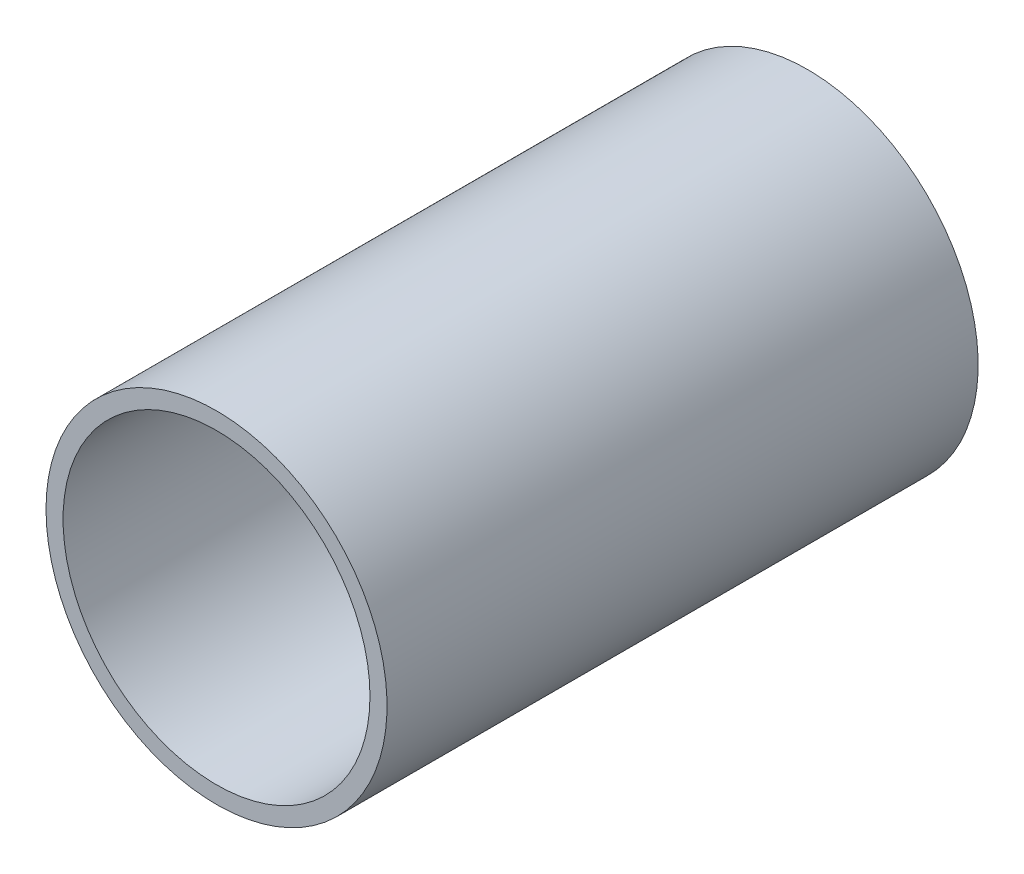
SolidWorks part; units mm, degrees
ref_plane "Front Plane" through (0, 0, 0) normal (0, 0, 1) x (1, 0, 0)
ref_plane "Top Plane" through (0, 0, 0) normal (0, 1, 0) x (1, 0, 0)
ref_plane "Right Plane" through (0, 0, 0) normal (1, 0, 0) x (0, 0, -1)
sketch "Sketch1" plane through (0, 0, 0) normal (0, 0, 1) x (1, 0, 0)
  circle A0 centre (0, 0) radius 15
  dimension "D1" = 30
extrude "Boss-Extrude1" add sketch "Sketch1" along normal blind 52
sketch "Sketch2" plane through (0, 0, 52) normal (0, 0, 1) x (1, 0, 0)
  circle A0 centre (0, 0) radius 13.5
  dimension "D1" = 27
extrude "Cut-Extrude1" cut sketch "Sketch2" against normal blind 48
